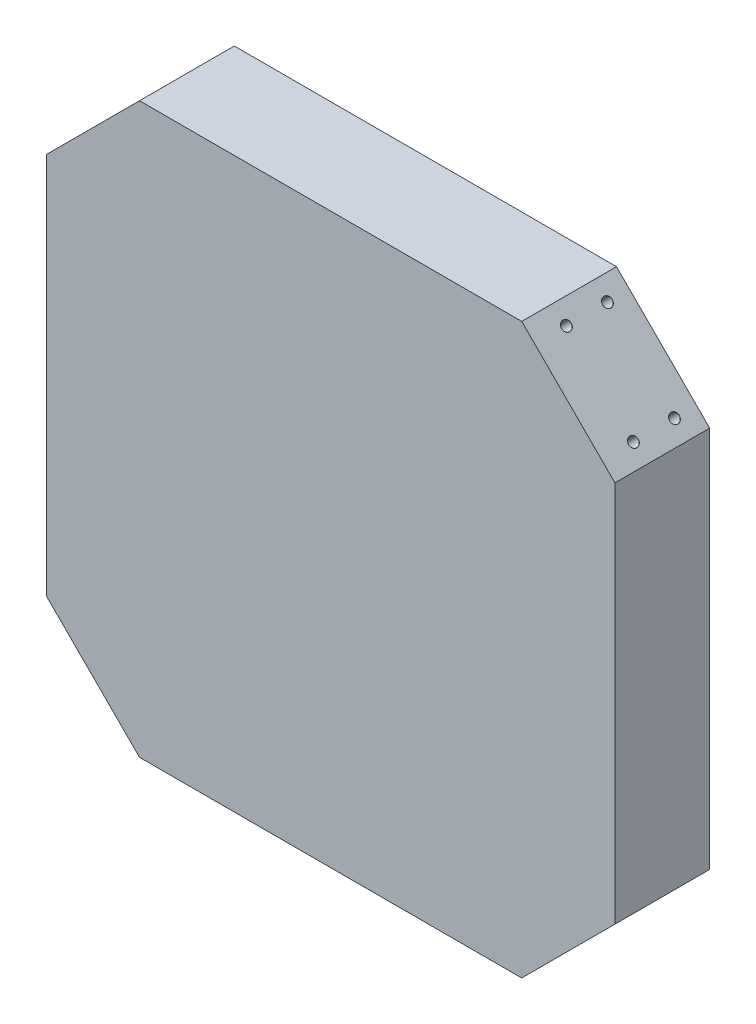
SolidWorks part; units mm, degrees
ref_plane "Front Plane" through (0, 0, 0) normal (0, 0, 1) x (1, 0, 0)
ref_plane "Top Plane" through (0, 0, 0) normal (0, 1, 0) x (1, 0, 0)
ref_plane "Right Plane" through (0, 0, 0) normal (1, 0, 0) x (0, 0, -1)
other "Center of Mass"
sketch "Sketch1" plane through (0, 0, 0) normal (0, 0, 1) x (1, 0, 0)
  line L0 (-60.4918, 90) -> (60.4918, 90)
  line L1 (60.4918, 90) -> (90, 60.4918)
  line L2 (90, 60.4918) -> (90, -60.4918)
  line L3 (90, -60.4918) -> (60.4918, -90)
  line L4 (60.4918, -90) -> (-60.4918, -90)
  line L5 (-60.4918, -90) -> (-90, -60.4918)
  line L6 (-90, -60.4918) -> (-90, 60.4918)
  line L7 (-90, 60.4918) -> (-60.4918, 90)
  line L8 (0, 85.791) -> (0, -113.7343) construction
  line L9 (123.1713, 0) -> (-157.8962, 0) construction
  dimension "D1" = 180
  dimension "D2" = 180
extrude "Boss-Extrude1" add sketch "Sketch1" along normal blind 30
shell "Shell1" thickness 5
hole_wizard "Ø3.0mm Dowel Hole1" positions "Sketch2" profile "Sketch3" hole size "Ø3.0" standard "DIN"
sketch "Sketch2" plane through (-75.2459, -75.2459, 0) normal (-0.7071, -0.7071, 0) x (-0.7071, 0.7071, 0)
  line L1 (20.8654, 0) -> (-20.8654, 0) construction
  line L2 (20.8654, -30) -> (-20.8654, -30) construction
  line L4 (0, 0) -> (0, -30) construction
  point P0 (-15, -7)
  point P2 (15, -7)
  point P4 (15, -20)
  point P6 (-15, -20)
  dimension "D1" = 7
  dimension "D2" = 10
  dimension "D3" = 30
sketch "Sketch3" plane through (-64.6393, -85.8525, 7) normal (0, 0, 1) x (0.7071, -0.7071, 0)
  line L0 (0, 0) -> (0, 30)
  line L1 (0, 30) -> (1.5, 29.0987)
  line L2 (1.5, 29.0987) -> (1.5, 0.025)
  line L3 (1.5, 0.025) -> (1.525, 0)
  line L5 (1.525, 0) -> (0, 0)
  line L6 (-1.5, 0.025) -> (-1.525, 0) construction
  line L10 (0, 30) -> (-1.5, 29.0987) construction
  line L11 (0, -6.35) -> (0, 107.95) construction
  dimension "Hole Dia." = 3
  dimension "Hole Depth" = 30
  dimension "Near C'Sink Dia." = 3.05
  dimension "Near C'Sink Angle" = 90
  dimension "Drill Angle" = 118
mirror "Mirror2" about plane through (0, 0, 0) normal (0, 1, 0) of "Ø3.0mm Dowel Hole1"
mirror "Mirror3" about plane through (0, 0, 0) normal (1, 0, 0) of "Mirror2", "Ø3.0mm Dowel Hole1"
sketch "Sketch4" plane through (0, 0, 25) normal (0, 0, -1) x (-1, 0, 0)
  line L0 (-58.4207, 85) -> (58.4207, 85)
  line L1 (58.4207, 85) -> (85, 58.4207)
  line L2 (85, 58.4207) -> (85, -58.4207)
  line L3 (85, -58.4207) -> (58.4207, -85)
  line L4 (-58.4207, -85) -> (-85, -58.4207)
  line L5 (-85, -58.4207) -> (-85, 58.4207)
  line L6 (-85, 58.4207) -> (-58.4207, 85)
  line L7 (58.4207, -85) -> (-58.4207, -85)
extrude "Boss-Extrude2" add sketch "Sketch4" along normal blind 3
sketch "Sketch5" plane through (0, 0, 22) normal (0, 0, -1) x (-1, 0, 0)
  line L1 (27.5, 85) -> (-27.5, 85)
  line L2 (27.5, 85) -> (27.5, -85)
  line L3 (27.5, -85) -> (-27.5, -85)
  line L4 (-27.5, 85) -> (-27.5, -85)
  line L5 (27.5, 85) -> (-27.5, -85) construction
  line L6 (27.5, -85) -> (-27.5, 85) construction
  line L9 (58.4207, 85) -> (-58.4207, 85) construction
  line L10 (-58.4207, -85) -> (58.4207, -85) construction
  point P0 (0, 0)
  dimension "D1" = 55
extrude "Cut-Extrude3" cut sketch "Sketch5" against normal blind 5
